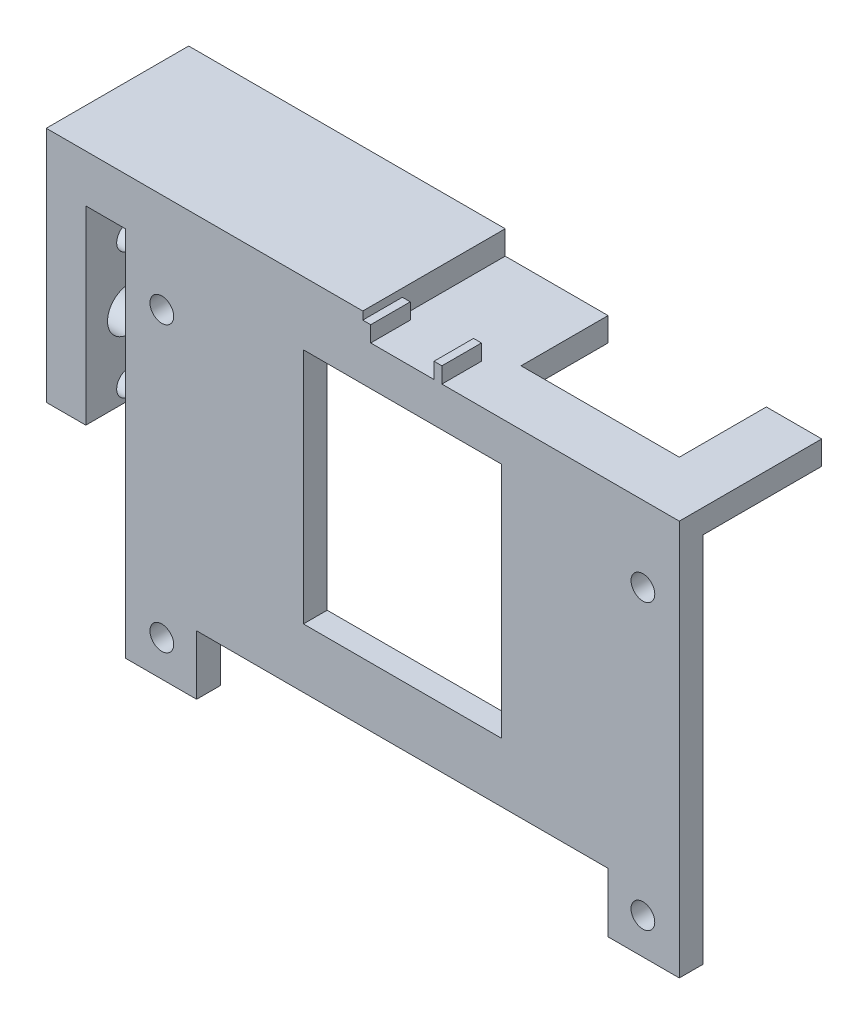
SolidWorks part; units mm, degrees
ref_plane "前视基准面" through (0, 0, 0) normal (0, 0, 1) x (1, 0, 0)
ref_plane "上视基准面" through (0, 0, 0) normal (0, 1, 0) x (1, 0, 0)
ref_plane "右视基准面" through (0, 0, 0) normal (1, 0, 0) x (0, 0, -1)
sketch "草图1" plane through (0, 0, 0) normal (0, 0, 1) x (1, 0, 0)
  line L1 (35, -22.5) -> (-35, -22.5)
  line L2 (35, -22.5) -> (35, 22.5)
  line L3 (35, 22.5) -> (-35, 22.5)
  line L4 (-35, -22.5) -> (-35, 22.5)
  line L5 (0, 22.5) -> (0, -22.5) construction
  line L6 (35, 0) -> (-35, 0) construction
  line L7 (26, -15) -> (-26, -15)
  line L8 (26, -15) -> (26, -22.5)
  line L9 (26, -22.5) -> (-26, -22.5)
  line L10 (-26, -15) -> (-26, -22.5)
  line L11 (0, -22.5) -> (0, -15) construction
  line L12 (26, -18.75) -> (-26, -18.75) construction
  line L13 (12.5, -7.5) -> (-12.5, -7.5)
  line L14 (12.5, -7.5) -> (12.5, 22.5)
  line L15 (12.5, 22.5) -> (-12.5, 22.5)
  line L16 (-12.5, -7.5) -> (-12.5, 22.5)
  line L17 (0, 22.5) -> (0, -7.5) construction
  line L18 (12.5, 7.5) -> (-12.5, 7.5) construction
  line L19 (-35, 22.5) -> (35, 22.5)
  line L20 (-35, 22.5) -> (-35, 24.5)
  line L21 (-35, 24.5) -> (35, 24.5)
  line L22 (35, 22.5) -> (35, 24.5)
  circle A0 centre (30.4, 17.95) radius 1.5
  circle A1 centre (30.4, -17.95) radius 1.5
  circle A2 centre (-30.4, -17.95) radius 1.5
  circle A3 centre (-30.4, 17.95) radius 1.5
  point P0 (0, 0)
  point P6 (0, -18.75)
  point P22 (0, 7.5)
  dimension "D3" = 3
  dimension "D4" = 35.9
  dimension "D5" = 60.8
  dimension "D1" = 70
  dimension "D2" = 45
  dimension "D6" = 7.5
  dimension "D7" = 52
  dimension "D8" = 30
  dimension "D9" = 25
  dimension "D10" = 2
extrude "凸台-拉伸1" add sketch "草图1" along normal blind 3 contours L10 L7 L8 L1 L2 L3 L4 A1 A0 A2 A3 | L20 L19 L22 L21
sketch "草图2" plane through (0, 24.5, 0) normal (0, 1, 0) x (1, 0, 0)
  line L1 (35, 19) -> (-35, 19)
  line L2 (35, 19) -> (35, -3)
  line L3 (35, -3) -> (-35, -3)
  line L4 (-35, 19) -> (-35, -3)
  line L5 (0, -3) -> (0, 19) construction
  line L6 (35, 8) -> (-35, 8) construction
  point P0 (0, 8)
  point P4 (0, 0)
  dimension "D1" = 22
extrude "凸台-拉伸2" add sketch "草图2" along normal blind 3
sketch "草图3" plane through (0, 27.5, 0) normal (0, 1, 0) x (1, 0, 0)
  line L0 (35, -3) -> (35, 19) construction
  line L1 (8, 25.549) -> (28, 25.549)
  line L2 (8, 25.549) -> (8, 4)
  line L3 (8, 4) -> (28, 4)
  line L4 (28, 25.549) -> (28, 4)
  line L6 (-35, -3) -> (35, -3) construction
  dimension "D1" = 20
  dimension "D2" = 27
  dimension "D3" = 7
extrude "切除-拉伸1" cut sketch "草图3" against normal blind 3
sketch "草图4" plane through (0, 0, 3) normal (0, 0, 1) x (1, 0, 0)
  line L0 (-35, 27.5) -> (35, 27.5) construction
  line L1 (4, 25.5) -> (-4, 25.5)
  line L2 (4, 25.5) -> (4, 29.5)
  line L3 (4, 29.5) -> (-4, 29.5)
  line L4 (-4, 25.5) -> (-4, 29.5)
  line L5 (0, 29.5) -> (0, 25.5) construction
  line L6 (4, 27.5) -> (-4, 27.5) construction
  line L8 (5, 25.5) -> (-5, 25.5)
  line L9 (5, 25.5) -> (5, 29.5)
  line L10 (5, 29.5) -> (-5, 29.5)
  line L11 (-5, 25.5) -> (-5, 29.5)
  line L12 (0, 29.5) -> (0, 25.5) construction
  line L13 (5, 27.5) -> (-5, 27.5) construction
  point P0 (0, 27.5)
  point P6 (0, 27.5)
  line M4 (35, 27.5) -> (-35, 27.5)
  dimension "D1" = 8
  dimension "D2" = 10
  dimension "D3" = 4
extrude "凸台-拉伸3" add sketch "草图4" against normal blind 5 contours L9 L10 L2 M4 | L11 L4 L10 M4
sketch "草图5" plane through (0, 27.5, 0) normal (0, 1, 0) x (1, 0, 0)
  line L5 (-35, -3) -> (-5, -3) construction
  line L6 (-5, -10) -> (-45, -10)
  line L11 (-5, -10) -> (-5, 15)
  line L12 (-5, 15) -> (-45, 15)
  line L13 (-45, -10) -> (-45, 15)
  line L14 (-5, 2) -> (-5, -3) construction
  line L15 (-35, 19) -> (-35, -3) construction
  dimension "D1" = 25
  dimension "D2" = 7
  dimension "D3" = 10
extrude "凸台-拉伸4" add sketch "草图5" along normal blind 3
sketch "草图6" plane through (0, 27.5, 0) normal (0, 1, 0) x (1, 0, 0)
  line L0 (-5, 15) -> (-45, 15) construction
  line L1 (-35, 19) -> (44.8087, 19)
  line L2 (-35, 19) -> (-35, 15)
  line L3 (-35, 15) -> (44.8087, 15)
  line L4 (44.8087, 19) -> (44.8087, 15)
extrude "切除-拉伸2" cut sketch "草图6" against normal blind 5
sketch "草图7" plane through (0, 30.5, 0) normal (0, 1, 0) x (1, 0, 0)
  line L0 (-45, -10) -> (-5, -10) construction
  line L1 (-45, 15) -> (-40, 15)
  line L2 (-45, 15) -> (-45, -10)
  line L3 (-45, -10) -> (-40, -10)
  line L4 (-40, 15) -> (-40, -10)
  dimension "D1" = 5
extrude "凸台-拉伸5" add sketch "草图7" against normal blind 30
sketch "草图8" plane through (-45, 0, 0) normal (-1, 0, 0) x (0, 0, 1)
  line L0 (-15, 30.5) -> (-15, 0.5) construction
  line L2 (10, 8.5651) -> (10, 17.9065) construction
  line L4 (-15, 8.5651) -> (-15, 17.9065) construction
  line L7 (10, 30.5) -> (10, 0.5) construction
  line L8 (-15, 0.5) -> (10, 0.5) construction
  circle A0 centre (-2.5, 10.5) radius 8 construction
  circle A1 centre (-2.5, 10.5) radius 2.75
  circle A2 centre (-2.5, 18.5) radius 1.6
  circle A6 centre (5.5, 10.5) radius 1.6
  circle A7 centre (-2.5, 2.5) radius 1.6
  circle A8 centre (-10.5, 10.5) radius 1.6
  point P0 (-2.5, 13.2358)
  point P25 (-1.5, 9.5)
  point P26 (-2.5, 10.5)
  dimension "D1" = 16
  dimension "D2" = 5.5
  dimension "D3" = 3.2
  dimension "D4" = 10
  dimension "D5" = 12.5
  dimension "D6" = 4
extrude "切除-拉伸3" cut sketch "草图8" against normal blind 5
sketch "草图9" plane through (0, 27.5, 0) normal (0, -1, 0) x (1, 0, 0)
  line L1 (-40, 10) -> (-35, 10)
  line L2 (-40, 10) -> (-40, -15)
  line L3 (-40, -15) -> (-35, -15)
  line L4 (-35, 10) -> (-35, -15)
extrude "凸台-拉伸6" add sketch "草图9" along normal up to surface (3 mm away) up to face at (9, 24.5, -8.5)
sketch "草图10" plane through (-5, 0, 0) normal (1, 0, 0) x (0, 0, -1)
  line L0 (-3, -22.5) -> (-3, 27.5) construction
  line L1 (-10, 30.5) -> (-3, 30.5)
  line L2 (-10, 30.5) -> (-10, -8.6767)
  line L3 (-10, -8.6767) -> (-3, -8.6767)
  line L4 (-3, 30.5) -> (-3, -8.6767)
extrude "切除-拉伸4" cut sketch "草图10" against normal through all
